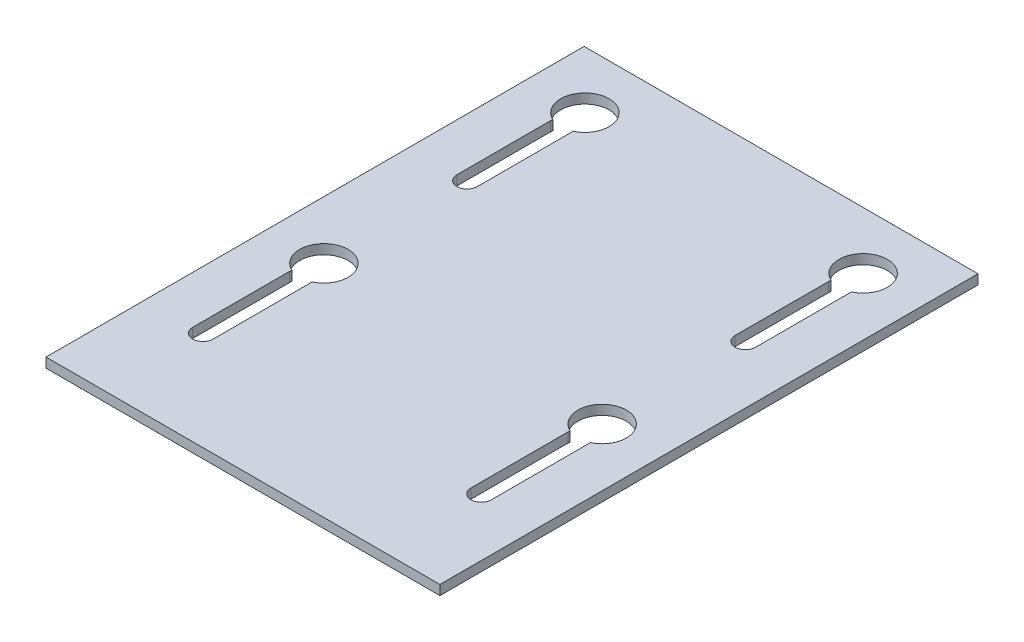
SolidWorks part; units mm, degrees
ref_plane "Front" through (0, 0, 0) normal (0, 0, 1) x (1, 0, 0)
ref_plane "Top" through (0, 0, 0) normal (0, 1, 0) x (1, 0, 0)
ref_plane "Right" through (0, 0, 0) normal (1, 0, 0) x (0, 0, -1)
sketch "Sketch3" plane through (0, 0, 0) normal (0, 1, 0) x (1, 0, 0)
  line L1 (0, 0) -> (122.1, 0)
  line L2 (0, 0) -> (0, 197.8)
  line L3 (0, 197.8) -> (122.1, 197.8)
  line L4 (122.1, 0) -> (122.1, 197.8)
  dimension "D1" = 122.1
  dimension "D2" = 197.8
extrude "Boss-Extrude2" add sketch "Sketch3" along normal blind 3
sketch "Sketch4" plane through (0, 3, 0) normal (0, 1, 0) x (1, 0, 0)
  line L1 (122.1, 197.8) -> (0, 197.8) construction
  line L2 (17.92, 160.62) -> (17.92, 131.62) construction
  line L3 (21.0877, 160.62) -> (21.0877, 131.62)
  line L4 (14.7523, 160.62) -> (14.7523, 131.62)
  line L5 (17.92, 79.72) -> (17.92, 49.72) construction
  line L6 (21.085, 79.72) -> (21.085, 49.72)
  line L7 (14.755, 79.72) -> (14.755, 49.72)
  line L8 (61.05, 197.8) -> (61.05, 0)
  line L9 (0, 0) -> (122.1, 0) construction
  line L10 (104.18, 79.72) -> (104.18, 49.72) construction
  line L11 (101.015, 79.72) -> (101.015, 49.72)
  line L12 (107.345, 79.72) -> (107.345, 49.72)
  line L13 (104.18, 160.62) -> (104.18, 131.62) construction
  line L14 (101.0123, 160.62) -> (101.0123, 131.62)
  line L15 (107.3477, 160.62) -> (107.3477, 131.62)
  line L16 (0, 197.8) -> (0, 0) construction
  circle A0 centre (17.92, 168.12) radius 7.5
  arc A1 (21.0877, 160.62) -> (14.7523, 160.62) centre (17.92, 160.62) ccw
  arc A2 (14.7523, 131.62) -> (21.0877, 131.62) centre (17.92, 131.62) ccw
  circle A3 centre (17.92, 87.22) radius 7.5
  arc A4 (21.085, 79.72) -> (14.755, 79.72) centre (17.92, 79.72) ccw
  arc A5 (14.755, 49.72) -> (21.085, 49.72) centre (17.92, 49.72) ccw
  arc A6 (101.015, 79.72) -> (107.345, 79.72) centre (104.18, 79.72) cw
  arc A7 (107.345, 49.72) -> (101.015, 49.72) centre (104.18, 49.72) cw
  circle A8 centre (104.18, 87.22) radius 7.5
  arc A9 (101.0123, 160.62) -> (107.3477, 160.62) centre (104.18, 160.62) cw
  arc A10 (107.3477, 131.62) -> (101.0123, 131.62) centre (104.18, 131.62) cw
  circle A11 centre (104.18, 168.12) radius 7.5
  point P8 (17.92, 146.12)
  point P17 (17.92, 64.72)
  point P28 (104.18, 64.72)
  point P37 (104.18, 146.12)
  point P44 (0, 0)
  dimension "D1" = 17.92
  dimension "D2" = 29.68
  dimension "D3" = 15
  dimension "D4" = 15
  dimension "D5" = 17.92
  dimension "D6" = 110.58
extrude "Cut-Extrude2" cut sketch "Sketch4" against normal blind 3 contours A1 A0 | A11 | L15 A10 L14 A9 | L6 A5 L7 A4 | A3 | A8 | L12 A7 L11 A6
sketch "Sketch5" plane through (0, 0, -197.8) normal (0, 0, -1) x (-1, 0, 0)
  line L1 (30.4256, -53.051) -> (-155.2134, -53.051)
  line L2 (30.4256, -53.051) -> (30.4256, 40.7636)
  line L3 (30.4256, 40.7636) -> (-155.2134, 40.7636)
  line L4 (-155.2134, -53.051) -> (-155.2134, 40.7636)
extrude "Cut-Extrude3" cut sketch "Sketch5" against normal blind 12
sketch "Sketch7" plane through (0, 0, 0) normal (0, 0, 1) x (1, 0, 0)
  line L1 (-24.4421, 90.1889) -> (157.5298, 90.1889)
  line L2 (-24.4421, 90.1889) -> (-24.4421, -71.4208)
  line L3 (-24.4421, -71.4208) -> (157.5298, -71.4208)
  line L4 (157.5298, 90.1889) -> (157.5298, -71.4208)
extrude "Cut-Extrude4" cut sketch "Sketch7" against normal blind 19
